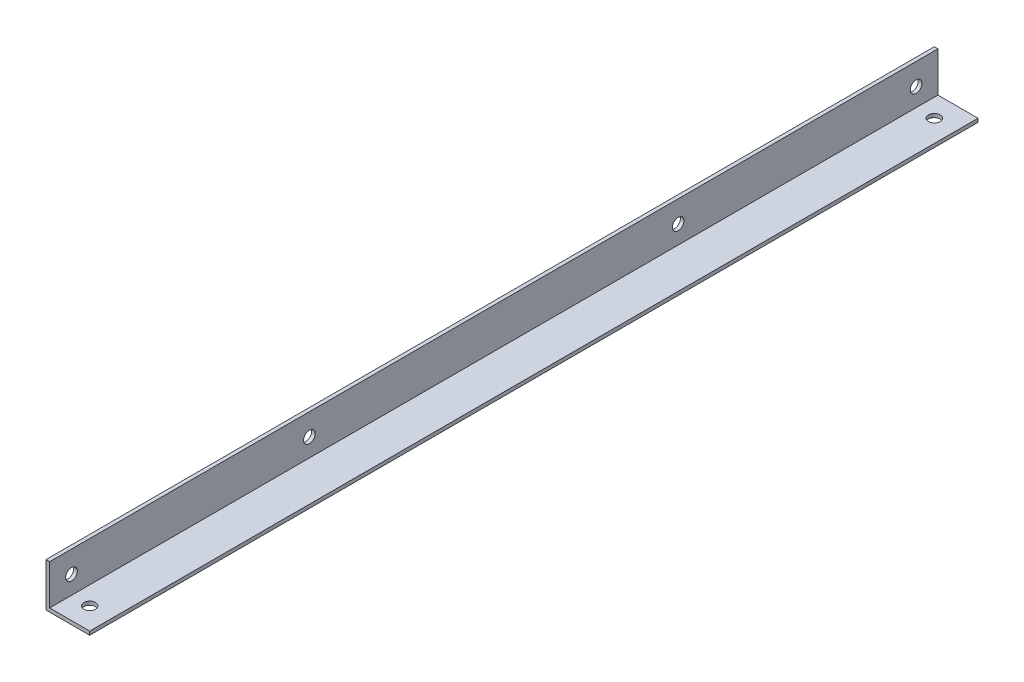
SolidWorks part; units mm, degrees
ref_plane "Front Plane" through (0, 0, 0) normal (0, 0, 1) x (1, 0, 0)
ref_plane "Top Plane" through (0, 0, 0) normal (0, 1, 0) x (1, 0, 0)
ref_plane "Right Plane" through (0, 0, 0) normal (1, 0, 0) x (0, 0, -1)
sketch "Sketch1" plane through (0, 0, 0) normal (0, 0, 1) x (1, 0, 0)
  line L0 (0, 0) -> (0, 30)
  line L1 (0, 30) -> (2.5, 30)
  line L2 (2.5, 30) -> (2.5, 2.5)
  line L3 (2.5, 2.5) -> (30, 2.5)
  line L4 (30, 2.5) -> (30, 0)
  line L5 (30, 0) -> (0, 0)
  dimension "D1" = 2.5
  dimension "D2" = 2.5
  dimension "D3" = 30
  dimension "D4" = 30
extrude "Boss-Extrude1" add sketch "Sketch1" along normal blind 609.6
sketch "Sketch2" plane through (2.5, 0, 0) normal (1, 0, 0) x (0, 0, -1)
  line L0 (0, 30) -> (0, 0) construction
  line L1 (-609.6, 30) -> (-609.6, 0) construction
  line L2 (-304.8, 82.2786) -> (-304.8, -92.2046) construction
  circle A0 centre (-594.6, 15) radius 4
  circle A1 centre (-15, 15) radius 4
  circle A2 centre (-431.3435, 15) radius 4
  circle A3 centre (-178.2565, 15) radius 4
  dimension "D2" = 8
  dimension "D3" = 15
  dimension "D4" = 15
  dimension "D5" = 8
  dimension "D1" = 304.8
  dimension "D6" = 163.2565
extrude "Cut-Extrude1" cut sketch "Sketch2" against normal through all
sketch "Sketch3" plane through (0, 2.5, 0) normal (0, 1, 0) x (1, 0, 0)
  line L0 (30, -609.6) -> (30, 0) construction
  line L1 (30, 0) -> (2.5, 0) construction
  line L2 (-108.1269, -304.8) -> (248.8441, -304.8) construction
  circle A0 centre (15, -15) radius 4
  circle A1 centre (15, -594.6) radius 4
  dimension "D1" = 8
  dimension "D5" = 15
  dimension "D2" = 15
  dimension "D3" = 15
  dimension "D4" = 304.8
extrude "Cut-Extrude2" cut sketch "Sketch3" against normal through all
sketch "Sketch4" plane through (2.5, 0, 0) normal (1, 0, 0) x (0, 0, -1)
  line L0 (-609.6, 2.5) -> (-609.6, 30) construction
  line L1 (-609.6, 30) -> (0, 30) construction
  line L2 (-304.8, 133.3632) -> (-304.8, -95.9027) construction
  circle A0 centre (-432.7, 15) radius 4
  circle A1 centre (-176.9, 15) radius 4
  dimension "D2" = 8
  dimension "D1" = 176.9
  dimension "D3" = 15
  dimension "D4" = 304.8
